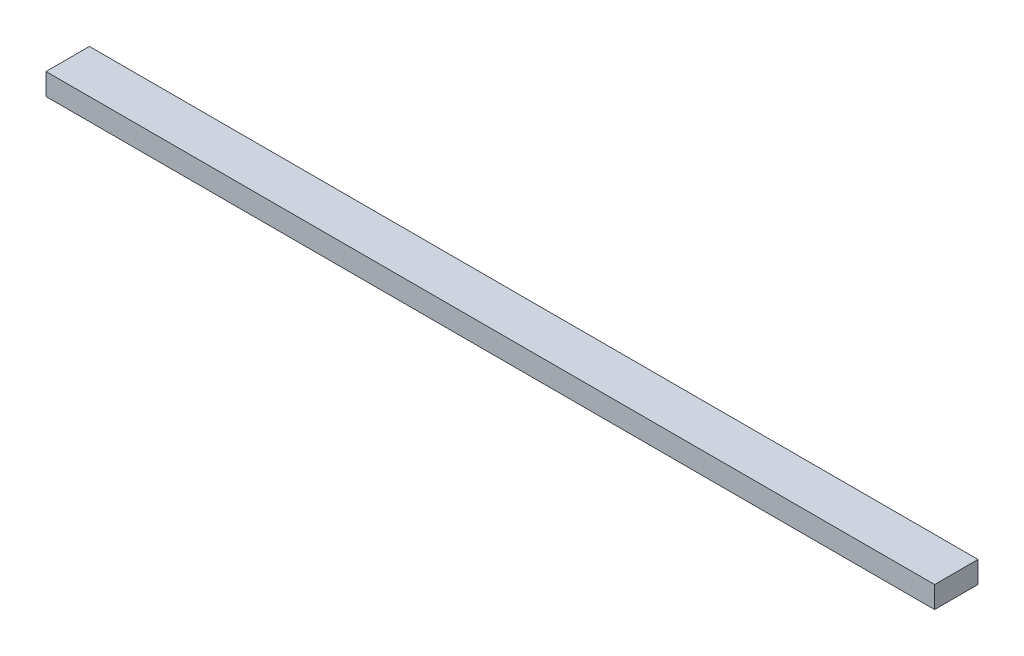
SolidWorks part; units mm, degrees
ref_plane "Front Plane" through (0, 0, 0) normal (0, 0, 1) x (1, 0, 0)
ref_plane "Top Plane" through (0, 0, 0) normal (0, 1, 0) x (1, 0, 0)
ref_plane "Right Plane" through (0, 0, 0) normal (1, 0, 0) x (0, 0, -1)
sketch "Sketch1" plane through (0, 0, 0) normal (1, 0, 0) x (0, 0, -1)
  line L1 (-3.175, -1.5875) -> (3.175, -1.5875) construction
  line L2 (-3.175, -1.5875) -> (-3.175, 1.5875) construction
  line L3 (-3.175, 1.5875) -> (3.175, 1.5875) construction
  line L4 (3.175, -1.5875) -> (3.175, 1.5875) construction
  line L5 (-3.175, -1.5875) -> (3.175, 1.5875) construction
  line L6 (-3.175, 1.5875) -> (3.175, -1.5875) construction
  point P0 (0, 0)
  dimension "Width" = 6.35
  dimension "Thickness" = 3.175
sketch "Sketch2" plane through (0, 0, 0) normal (0, 0, 1) x (1, 0, 0)
  line L0 (-65, 0) -> (65, 0) construction
  point P4 (0, 0)
  dimension "Length" = 130
sketch "Sketch3" plane through (0, 0, 0) normal (1, 0, 0) x (0, 0, -1)
  line L0 (3.175, -1.5875) -> (3.175, 1.5875) construction
  line L1 (-3.175, -1.5875) -> (3.175, -1.5875) construction
  line L2 (-3.175, -1.5875) -> (-3.175, 1.5875) construction
  line L3 (-3.175, 1.5875) -> (3.175, 1.5875) construction
  line L4 (3.175, -1.5875) -> (3.175, 1.5875)
  line L5 (-3.175, -1.5875) -> (3.175, -1.5875)
  line L6 (-3.175, -1.5875) -> (-3.175, 1.5875)
  line L7 (-3.175, 1.5875) -> (3.175, 1.5875)
extrude "Boss-Extrude1" add sketch "Sketch3" along normal up to vertex (65 mm away) and the other way up to vertex (65 mm away) up to point (65, 0, 0) other way up to point (-65, 0, 0)
